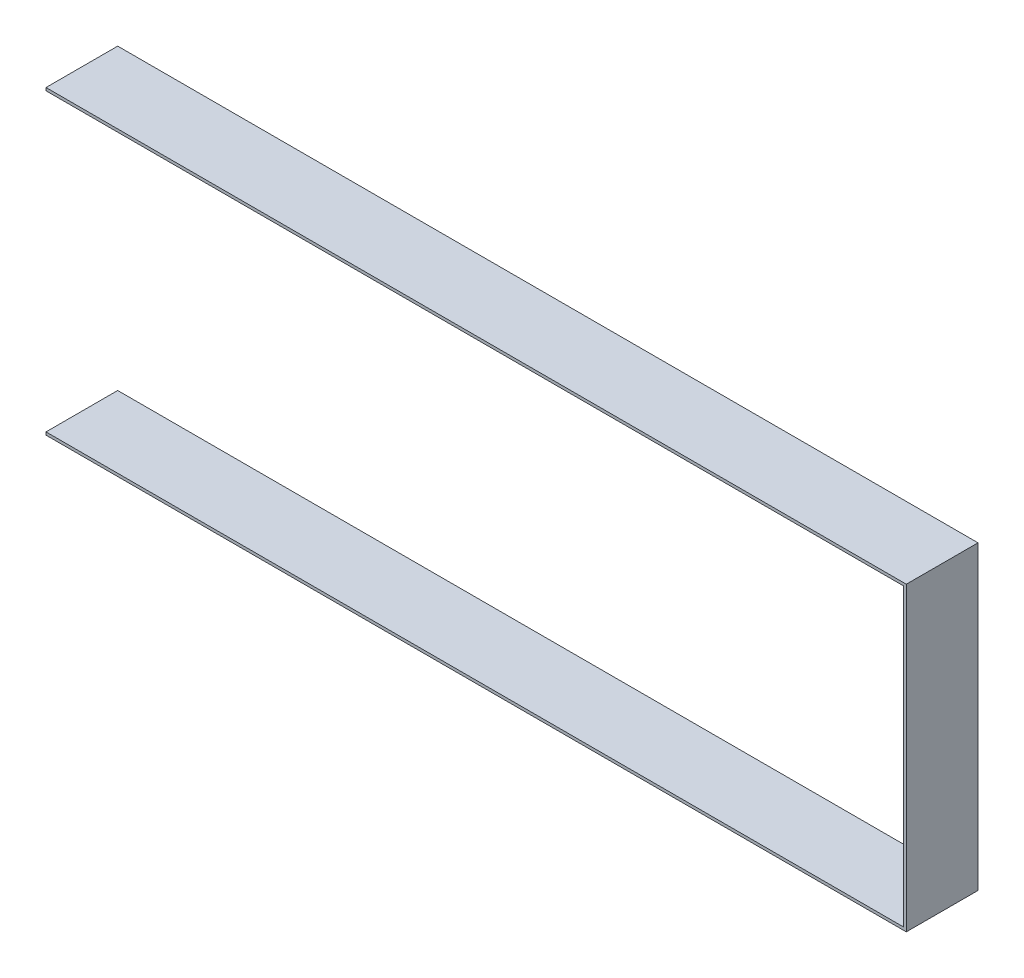
SolidWorks part; units mm, degrees
ref_plane "Front Plane" through (0, 0, 0) normal (0, 0, 1) x (1, 0, 0)
ref_plane "Top Plane" through (0, 0, 0) normal (0, 1, 0) x (1, 0, 0)
ref_plane "Right Plane" through (0, 0, 0) normal (1, 0, 0) x (0, 0, -1)
sketch "Sketch2" plane through (0, 0, 0) normal (0, 0, 1) x (1, 0, 0)
  line L0 (-2.0743, 0) -> (74.1257, 0)
  line L1 (74.1257, 0) -> (74.1257, 26.67)
  line L2 (74.1257, 26.67) -> (-2.0743, 26.67)
  line L3 (-2.0743, 26.67) -> (-2.0743, 26.416)
  line L4 (-2.0743, 26.416) -> (73.8717, 26.416)
  line L5 (73.8717, 26.416) -> (73.8717, 0.254)
  line L6 (73.8717, 0.254) -> (-2.0743, 0.254)
  line L7 (-2.0743, 0.254) -> (-2.0743, 0)
  dimension "D1" = 0.254
  dimension "D2" = 0.254
  dimension "D3" = 0.254
  dimension "D4" = 76.2
  dimension "D5" = 76.2
  dimension "D6" = 26.67
  dimension "D7" = 0.254
extrude "Boss-Extrude1" add sketch "Sketch2" along normal blind 6.35
